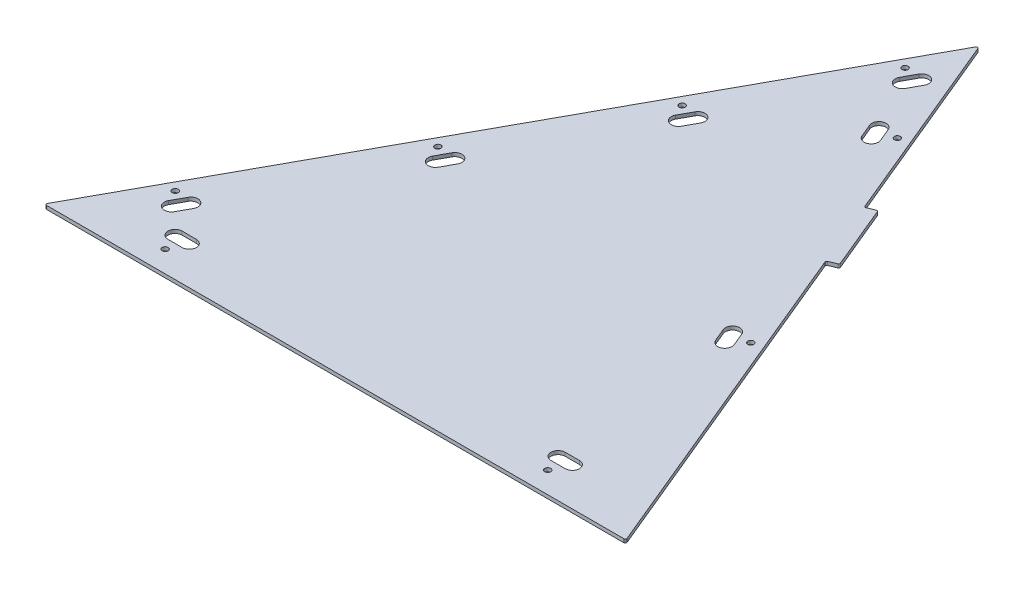
SolidWorks part; units mm, degrees
material "PE High Density"
ref_plane "Front Plane" through (0, 0, 0) normal (0, 0, 1) x (1, 0, 0)
ref_plane "Top Plane" through (0, 0, 0) normal (0, 1, 0) x (1, 0, 0)
ref_plane "Right Plane" through (0, 0, 0) normal (1, 0, 0) x (0, 0, -1)
sketch "Sketch4" plane through (0, 0, 0) normal (0, 1, 0) x (1, 0, 0)
  line L0 (-356.1703, 0) -> (682.6897, 0)
  line L1 (682.6897, 0) -> (234.9792, 1078.9716)
  line L2 (234.9792, 1078.9716) -> (-356.1703, 0)
  line L3 (381.0003, 727.0642) -> (398.5957, 734.3653)
  line L4 (398.5957, 734.3653) -> (447.2694, 617.0628)
  line L5 (447.2694, 617.0628) -> (429.674, 609.7617)
  line L6 (429.674, 609.7617) -> (381.0003, 727.0642)
  line L9 (664.3232, 0) -> (-326.0136, 0) construction
  circle A2 centre (303.6675, 863.7291) radius 5.3578
  circle A3 centre (489.2933, 416.3753) radius 5.3578
  circle A5 centre (61.0945, 721.9489) radius 5.3578
  circle A6 centre (-93.2898, 440.1652) radius 5.3578
  circle A7 centre (-259.301, 137.16) radius 5.3578
  circle A9 centre (504.8897, 38.1) radius 5.3578
  circle A10 centre (-178.3703, 38.1) radius 5.3578
  circle A11 centre (201.9739, 979.0832) radius 5.3578
  dimension "D4" = 10.7156
  dimension "D5" = 19.05
  dimension "D6" = 10.7156
  dimension "D10" = 10.7156
  dimension "D12" = 10.7156
  dimension "D13" = 127
  dimension "D14" = 10.7156
  dimension "D15" = 10.7156
  dimension "D16" = 10.7156
  dimension "D1" = 1038.86
  dimension "D2" = 1168.1714
  dimension "D3" = 1230.2998
  dimension "D7" = 19.05
  dimension "D8" = 19.05
  dimension "D9" = 19.05
  dimension "D11" = 38.1
  dimension "D17" = 137.16
  dimension "D18" = 381
  dimension "D20" = 38.1
  dimension "D21" = 177.8
  dimension "D22" = 19.05
  dimension "D23" = 19.05
  dimension "D24" = 177.8
  dimension "D25" = 19.05
extrude "Boss-Extrude2" add sketch "Sketch4" along normal blind 6.35
sketch "Sketch5" plane through (0, 6.35, 0) normal (0, 1, 0) x (1, 0, 0)
  line L0 (-239.2238, 110.3702) -> (-227.0193, 132.6459) construction
  line L1 (-250.3617, 116.4724) -> (-238.1571, 138.7482)
  line L2 (-228.0859, 104.2679) -> (-215.8814, 126.5437)
  line L3 (-191.0703, 68.58) -> (-165.6703, 68.58) construction
  line L4 (-191.0703, 81.28) -> (-165.6703, 81.28)
  line L5 (-191.0703, 55.88) -> (-165.6703, 55.88)
  line L6 (-72.3558, 414.9391) -> (-60.1513, 437.2149) construction
  line L7 (-83.4937, 421.0413) -> (-71.2892, 443.3171)
  line L8 (-61.2179, 408.8368) -> (-49.0134, 431.1126)
  line L9 (222.745, 953.5599) -> (234.9496, 975.8357) construction
  line L10 (211.6072, 959.6622) -> (223.8117, 981.9379)
  line L11 (233.8829, 947.4576) -> (246.0874, 969.7334)
  line L12 (81.2069, 695.2231) -> (93.4668, 717.6001) construction
  line L13 (70.069, 701.3254) -> (82.3289, 723.7023)
  line L14 (92.3448, 689.1209) -> (104.6047, 711.4978)
  line L15 (270.6329, 863.8128) -> (280.3677, 840.3524) construction
  line L18 (456.0343, 416.9998) -> (465.7691, 393.5393) construction
  line L19 (467.7646, 421.8672) -> (477.4993, 398.4067)
  line L20 (444.3041, 412.1325) -> (454.0388, 388.672)
  line L21 (492.9613, 68.58) -> (518.3613, 68.58) construction
  line L22 (492.9613, 81.28) -> (518.3613, 81.28)
  line L23 (492.9613, 55.88) -> (518.3613, 55.88)
  line L24 (234.9792, 1078.9716) -> (-356.1703, 0) construction
  line L25 (-356.1703, 0) -> (682.6897, 0) construction
  line L26 (282.3632, 868.6802) -> (292.0979, 845.2197)
  line L27 (258.9027, 858.9455) -> (268.6374, 835.485)
  line L28 (682.6897, 0) -> (429.674, 609.7617) construction
  line L29 (381.0003, 727.0642) -> (234.9792, 1078.9716) construction
  arc A0 (-250.3617, 116.4724) -> (-228.0859, 104.2679) centre (-239.2238, 110.3702) ccw
  arc A1 (-215.8814, 126.5437) -> (-238.1571, 138.7482) centre (-227.0193, 132.6459) ccw
  arc A2 (-191.0703, 81.28) -> (-191.0703, 55.88) centre (-191.0703, 68.58) ccw
  arc A3 (-165.6703, 55.88) -> (-165.6703, 81.28) centre (-165.6703, 68.58) ccw
  arc A4 (-83.4937, 421.0413) -> (-61.2179, 408.8368) centre (-72.3558, 414.9391) ccw
  arc A5 (-49.0134, 431.1126) -> (-71.2892, 443.3171) centre (-60.1513, 437.2149) ccw
  arc A6 (211.6072, 959.6622) -> (233.8829, 947.4576) centre (222.745, 953.5599) ccw
  arc A7 (246.0874, 969.7334) -> (223.8117, 981.9379) centre (234.9496, 975.8357) ccw
  arc A8 (70.069, 701.3254) -> (92.3448, 689.1209) centre (81.2069, 695.2231) ccw
  arc A9 (104.6047, 711.4978) -> (82.3289, 723.7023) centre (93.4668, 717.6001) ccw
  arc A12 (467.7646, 421.8672) -> (444.3041, 412.1325) centre (456.0343, 416.9998) ccw
  arc A13 (454.0388, 388.672) -> (477.4993, 398.4067) centre (465.7691, 393.5393) ccw
  arc A14 (492.9613, 81.28) -> (492.9613, 55.88) centre (492.9613, 68.58) ccw
  arc A15 (518.3613, 55.88) -> (518.3613, 81.28) centre (518.3613, 68.58) ccw
  circle A16 centre (-178.3703, 38.1) radius 5.3578 construction
  circle A17 centre (-259.301, 137.16) radius 5.3578 construction
  circle A18 centre (-93.2898, 440.1652) radius 5.3578 construction
  arc A19 (282.3632, 868.6802) -> (258.9027, 858.9455) centre (270.6329, 863.8128) ccw
  circle A20 centre (61.0945, 721.9489) radius 5.3578 construction
  arc A22 (268.6374, 835.485) -> (292.0979, 845.2197) centre (280.3677, 840.3524) ccw
  circle A23 centre (489.2933, 416.3753) radius 5.3578 construction
  circle A24 centre (504.8897, 38.1) radius 5.3578 construction
  circle A25 centre (201.9739, 979.0832) radius 5.3578 construction
  circle A26 centre (303.6675, 863.7291) radius 5.3578 construction
  point P2 (-233.1215, 121.5081)
  point P7 (-178.3703, 68.58)
  point P14 (-66.2536, 426.077)
  point P21 (228.8473, 964.6978)
  point P28 (87.3369, 706.4116)
  point P35 (275.5003, 852.0826)
  point P42 (460.9017, 405.2696)
  point P49 (505.6613, 68.58)
  dimension "D9" = 17.78
  dimension "D10" = 17.78
  dimension "D6" = 17.78
  dimension "D1" = 25.4
  dimension "D2" = 25.4
  dimension "D3" = 17.78
  dimension "D4" = 17.78
  dimension "D5" = 17.78
  dimension "D7" = 17.78
  dimension "D8" = 17.78
  dimension "D11" = 121.5081
  dimension "D12" = 426.077
  dimension "D13" = 706.4116
  dimension "D14" = 114.2738
  dimension "D15" = 405.2696
extrude "Cut-Extrude1" cut sketch "Sketch5" against normal through all
fillet "Fillet1" radius 2.54 7 edges at (398.5957, 3.175, -734.3653) (447.2694, 3.175, -617.0628) (429.674, 3.175, -609.7617) (381.0003, 3.175, -727.0642) (682.6897, 3.175, 0) (-356.1703, 3.175, 0) (234.9792, 3.175, -1078.9716)
